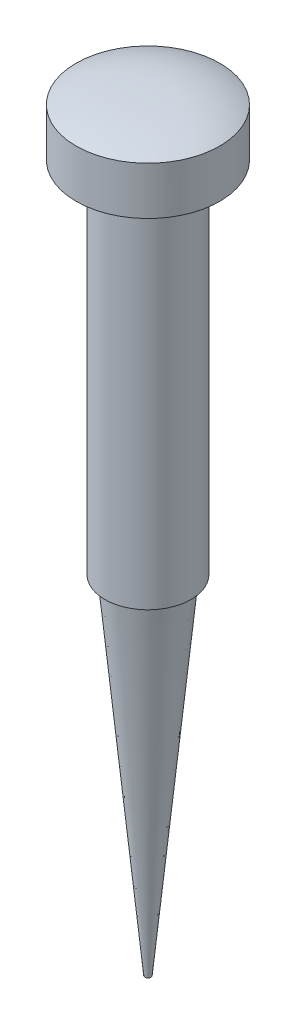
SolidWorks part; units mm, degrees
ref_plane "Front Plane" through (0, 0, 0) normal (0, 0, 1) x (1, 0, 0)
ref_plane "Top Plane" through (0, 0, 0) normal (0, 1, 0) x (1, 0, 0)
ref_plane "Right Plane" through (0, 0, 0) normal (1, 0, 0) x (0, 0, -1)
sketch "Sketch1" plane through (0, 0, 0) normal (0, 1, 0) x (1, 0, 0)
  circle A0 centre (0, 0) radius 1.8
  dimension "D1" = 3.6
extrude "Boss-Extrude1" add sketch "Sketch1" along normal blind 15
sketch "Sketch2" plane through (0, 15, 0) normal (0, 1, 0) x (1, 0, 0)
  circle A0 centre (0, 0) radius 3
  dimension "D1" = 6
extrude "Boss-Extrude2" add sketch "Sketch2" along normal blind 2
sketch "Sketch3" plane through (0, 0, 0) normal (0, 0, 1) x (1, 0, 0)
  line L0 (0, 17) -> (-3, 17)
  line L1 (3, 17) -> (-3, 17) construction
  line L2 (0, 17) -> (0, 17.5)
  line L3 (0.7768, 17.5) -> (-0.7768, 17.5) construction
  spline S0 degree 3 poles (-3, 17) (-2.0275, 17.4627) (-0.9711, 17.5) (0, 17.5) knots 0 0 0 0 1 1 1 1
  dimension "D1" = 0.5
revolve "Revolve1" add sketch "Sketch3" angle 360 about L2
sketch "Sketch4" plane through (0, 0, 0) normal (0, 0, 1) x (1, 0, 0)
  line L0 (0, 0) -> (1.5008, 0)
  line L1 (0, 0) -> (0, -14.5)
  line L6 (1.5008, 0) -> (0.125, -14.5)
  line L7 (0.125, -14.5) -> (0, -14.5)
  line L8 (1.8, 0) -> (1.8, 15) construction
  dimension "D1" = 0.125
  dimension "D2" = 14.5
  dimension "D3" = 5.42
revolve "Revolve3" add sketch "Sketch4" angle 360 about L1
